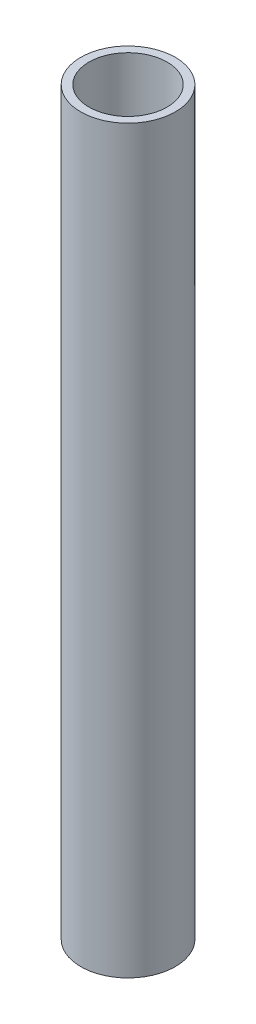
SolidWorks part; units mm, degrees
ref_plane "Front Plane" through (0, 0, 0) normal (0, 0, 1) x (1, 0, 0)
ref_plane "Top Plane" through (0, 0, 0) normal (0, 1, 0) x (1, 0, 0)
ref_plane "Right Plane" through (0, 0, 0) normal (1, 0, 0) x (0, 0, -1)
sketch "Sketch1" plane through (0, 0, 0) normal (0, 1, 0) x (1, 0, 0)
  circle A0 centre (0, 0) radius 19
  circle A1 centre (0, 0) radius 23
  dimension "D1" = 38
  dimension "D3" = 46
  dimension "D2" = 4
extrude "Boss-Extrude1" add sketch "Sketch1" along normal blind 360
